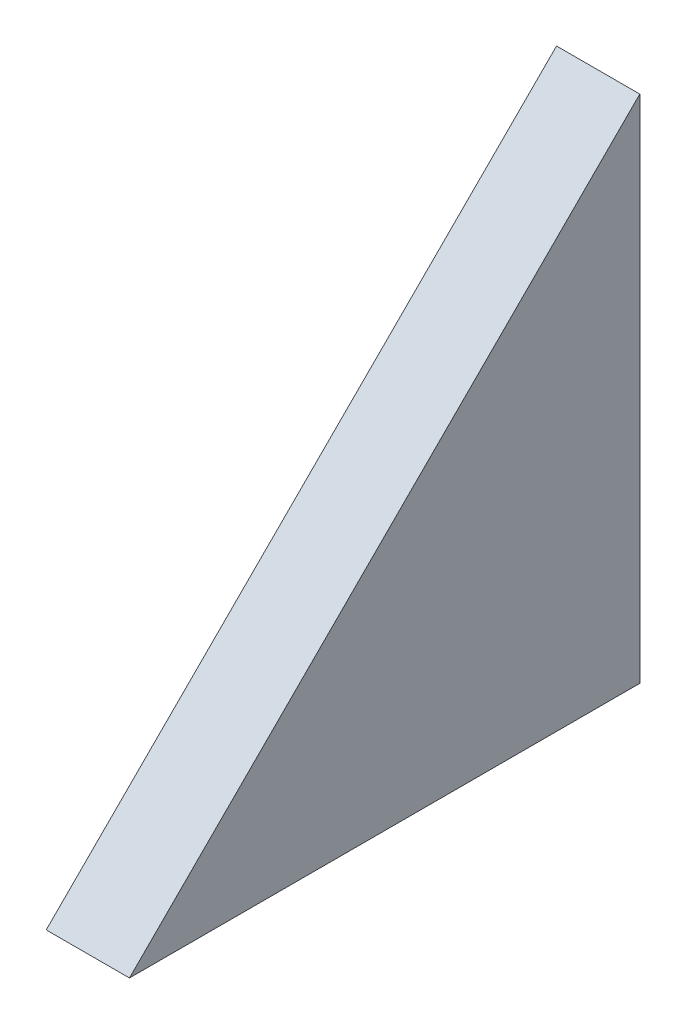
SolidWorks part; units mm, degrees
ref_plane "Front Plane" through (0, 0, 0) normal (0, 0, 1) x (1, 0, 0)
ref_plane "Top Plane" through (0, 0, 0) normal (0, 1, 0) x (1, 0, 0)
ref_plane "Right Plane" through (0, 0, 0) normal (1, 0, 0) x (0, 0, -1)
sketch "Sketch1" plane through (0, 0, 0) normal (1, 0, 0) x (0, 0, -1)
  line L0 (-39.5228, 96.9547) -> (-156.2661, -19.7886)
  line L1 (-156.2661, -19.7886) -> (-39.5228, -19.7886)
  line L2 (-39.5228, 96.9547) -> (-39.5228, -19.7886)
  point P2 (0, 0)
  point P4 (-213.1409, 17.8047)
  dimension "D1" = 45
extrude "Boss-Extrude1" add sketch "Sketch1" along normal blind 19.05 contours L2 L1 L0
